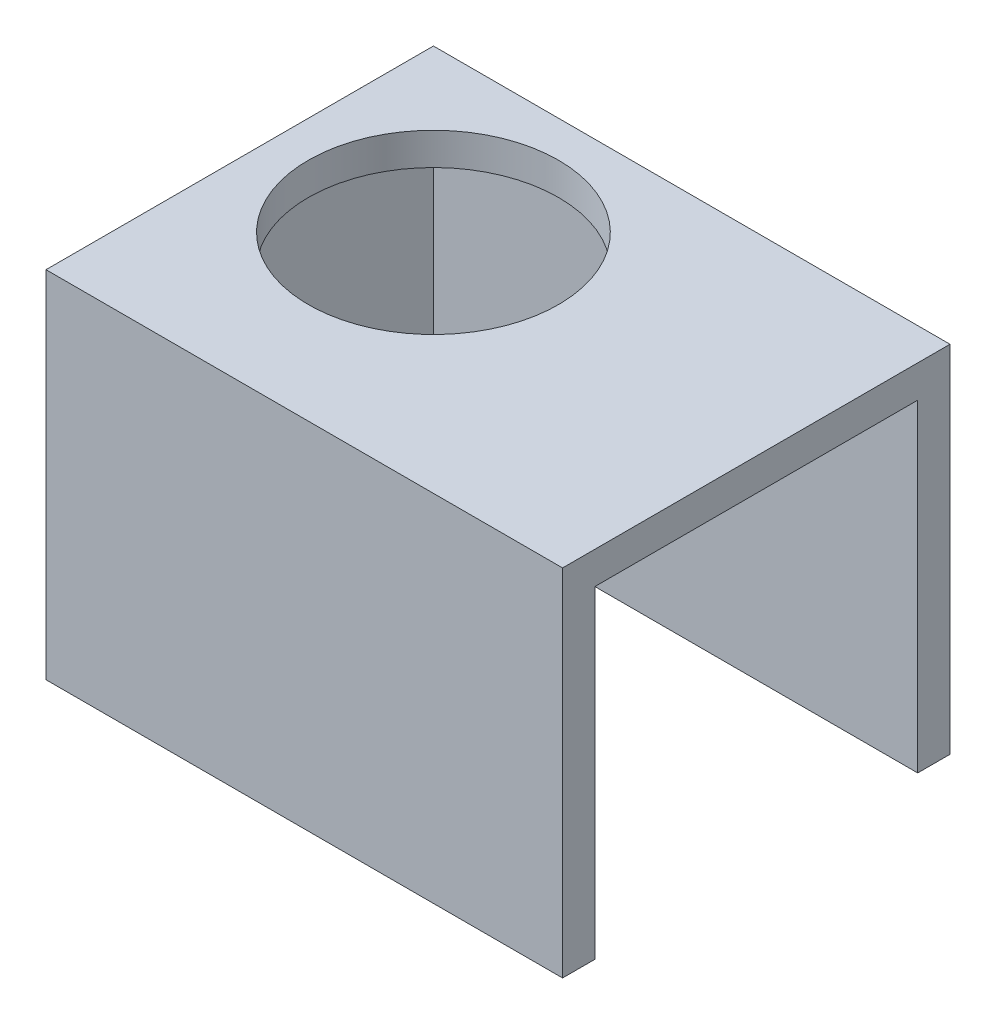
SolidWorks part; units mm, degrees
ref_plane "Alzado" through (0, 0, 0) normal (0, 0, 1) x (1, 0, 0)
ref_plane "Planta" through (0, 0, 0) normal (0, 1, 0) x (1, 0, 0)
ref_plane "Vista lateral" through (0, 0, 0) normal (1, 0, 0) x (0, 0, -1)
sketch "Croquis1" plane through (0, 0, 0) normal (0, 1, 0) x (1, 0, 0)
  line L1 (-16, -12) -> (16, -12)
  line L2 (-16, -12) -> (-16, 12)
  line L3 (-16, 12) -> (16, 12)
  line L4 (16, -12) -> (16, 12)
  line L5 (-16, -12) -> (16, 12) construction
  line L6 (-16, 12) -> (16, -12) construction
  point P0 (0, 0)
  dimension "D1" = 24
  dimension "D2" = 32
extrude "Saliente-Extruir1" add sketch "Croquis1" along normal blind 24
shell "Vaciado1" thickness 2
sketch "Croquis2" plane through (0, 22, 0) normal (0, -1, 0) x (-1, 0, 0)
  line L0 (16, 12) -> (16, -12) construction
  line L2 (-16, 12) -> (16, 12) construction
  circle A0 centre (6, 2) radius 7.75
  point P6 (11.4491, 11.7736)
  dimension "D3" = 15.5
  dimension "D1" = 10
  dimension "D2" = 10
extrude "Cortar-Extruir1" cut sketch "Croquis2" against normal blind 5
sketch "Croquis3" plane through (0, 0, 0) normal (0, -1, 0) x (-1, 0, 0)
  line L1 (16, -12) -> (-16, -12)
  line L2 (16, -12) -> (16, 12)
  line L3 (16, 12) -> (-16, 12)
  line L4 (-16, -12) -> (-16, 12)
  line L5 (16, -12) -> (-16, 12) construction
  line L6 (16, 12) -> (-16, -12) construction
  point P0 (0, 0)
extrude "Cortar-Extruir2" cut sketch "Croquis3" against normal blind 2
